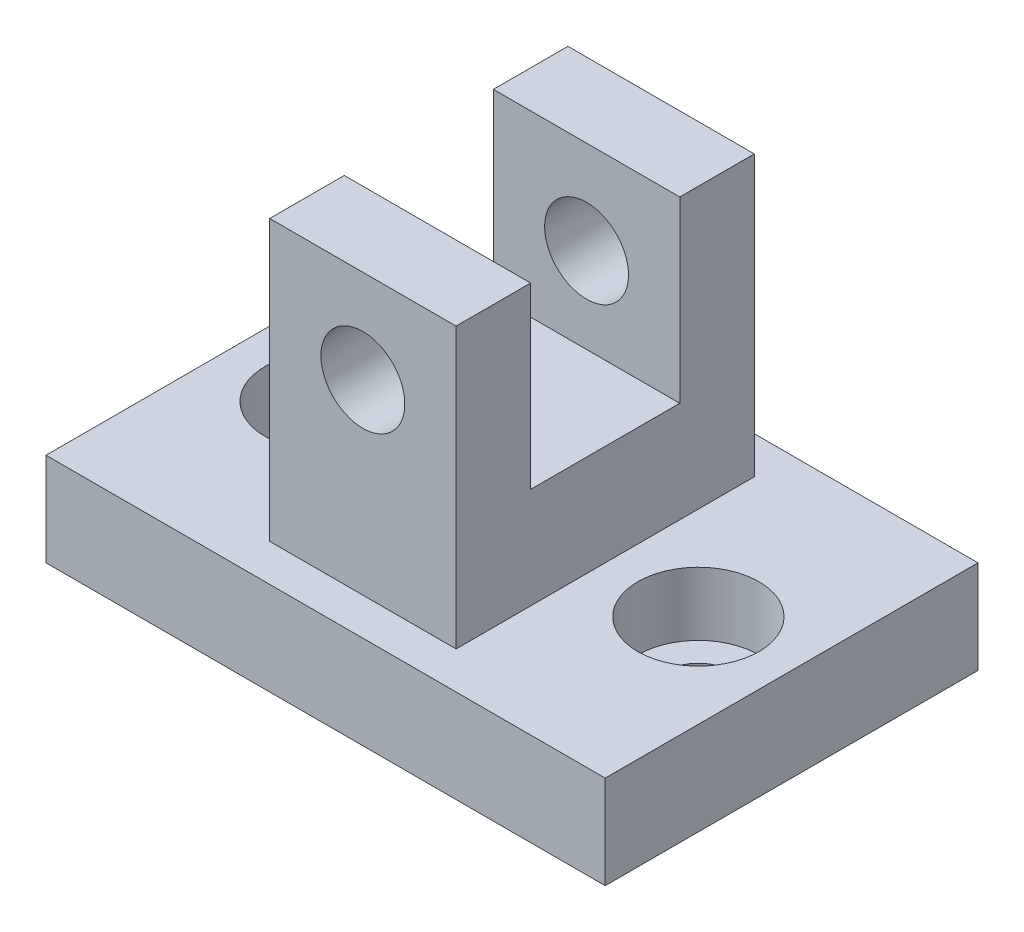
SolidWorks part; units mm, degrees
material "ABS"
ref_plane "Front Plane" through (0, 0, 0) normal (0, 0, 1) x (1, 0, 0)
ref_plane "Top Plane" through (0, 0, 0) normal (0, 1, 0) x (1, 0, 0)
ref_plane "Right Plane" through (0, 0, 0) normal (1, 0, 0) x (0, 0, -1)
sketch "Sketch1" plane through (0, 0, 0) normal (0, 1, 0) x (1, 0, 0)
  line L1 (-15, -10) -> (15, -10)
  line L2 (-15, -10) -> (-15, 10)
  line L3 (-15, 10) -> (15, 10)
  line L4 (15, -10) -> (15, 10)
  line L5 (-15, -10) -> (15, 10) construction
  line L6 (-15, 10) -> (15, -10) construction
  point P0 (0, 0)
  dimension "D1" = 20
  dimension "D2" = 30
extrude "Boss-Extrude1" add sketch "Sketch1" along normal blind 5
sketch "Sketch2" plane through (0, 5, 0) normal (0, 1, 0) x (1, 0, 0)
  line L1 (-5, -8) -> (5, -8)
  line L2 (-5, -8) -> (-5, 8)
  line L3 (-5, 8) -> (5, 8)
  line L4 (5, -8) -> (5, 8)
  line L5 (-5, -8) -> (5, 8) construction
  line L6 (-5, 8) -> (5, -8) construction
  point P0 (0, 0)
  dimension "D1" = 10
  dimension "D2" = 16
extrude "Boss-Extrude2" add sketch "Sketch2" along normal blind 15
sketch "Sketch3" plane through (-5, 0, 0) normal (-1, 0, 0) x (0, 0, 1)
  line L0 (-8, 20) -> (8, 20) construction
  line L1 (-4, 20) -> (4, 20)
  line L2 (-4, 20) -> (-4, 10.4139)
  line L3 (-4, 10.4139) -> (4, 10.4139)
  line L4 (4, 20) -> (4, 10.4139)
  line L5 (-8, 20) -> (-8, 5) construction
  dimension "D1" = 8
  dimension "D2" = 4
extrude "Cut-Extrude1" cut sketch "Sketch3" against normal through all
sketch "Sketch4" plane through (0, 0, -8) normal (0, 0, -1) x (-1, 0, 0)
  line L0 (-5, 5) -> (5, 5) construction
  circle A0 centre (0, 15) radius 2.25
  dimension "D1" = 4.5
  dimension "D2" = 10
extrude "Cut-Extrude2" cut sketch "Sketch4" against normal through all
sketch "Sketch5" plane through (0, 5, 0) normal (0, 1, 0) x (1, 0, 0)
  line L0 (15, -10) -> (15, 10) construction
  line L1 (-15, 10) -> (-15, -10) construction
  circle A0 centre (-10, 0) radius 1.75
  circle A1 centre (10, 0) radius 1.75
  dimension "D1" = 3.5
  dimension "D2" = 3.5
  dimension "D3" = 5
  dimension "D4" = 5
extrude "Cut-Extrude3" cut sketch "Sketch5" against normal blind 15
hole_wizard "CBORE for M3 Hex Socket Head Cap Screw1" positions "Sketch6" profile "Sketch7" counterbore size "M3" standard "ISO" end condition through all
sketch "Sketch6" plane through (0, 5, 0) normal (0, 1, 0) x (1, 0, 0)
  point P0 (-10, 0)
  point P3 (10, 0)
sketch "Sketch7" plane through (-10, 5, 0) normal (1, 0, 0) x (0, 0, 1)
  line L0 (0, 0) -> (0, 5)
  line L1 (0, 5) -> (1.7, 5)
  line L3 (1.7, 5) -> (1.7, 3.4)
  line L4 (1.7, 3.4) -> (3.25, 3.4)
  line L5 (3.25, 3.4) -> (3.25, 0)
  line L7 (3.25, 0) -> (0, 0)
  line L11 (0, -6.35) -> (0, 107.95) construction
  dimension "Thru Hole Dia." = 3.4
  dimension "Thru Hole Depth" = 5
  dimension "C'Bore Dia." = 6.5
  dimension "C'Bore Depth" = 3.4
